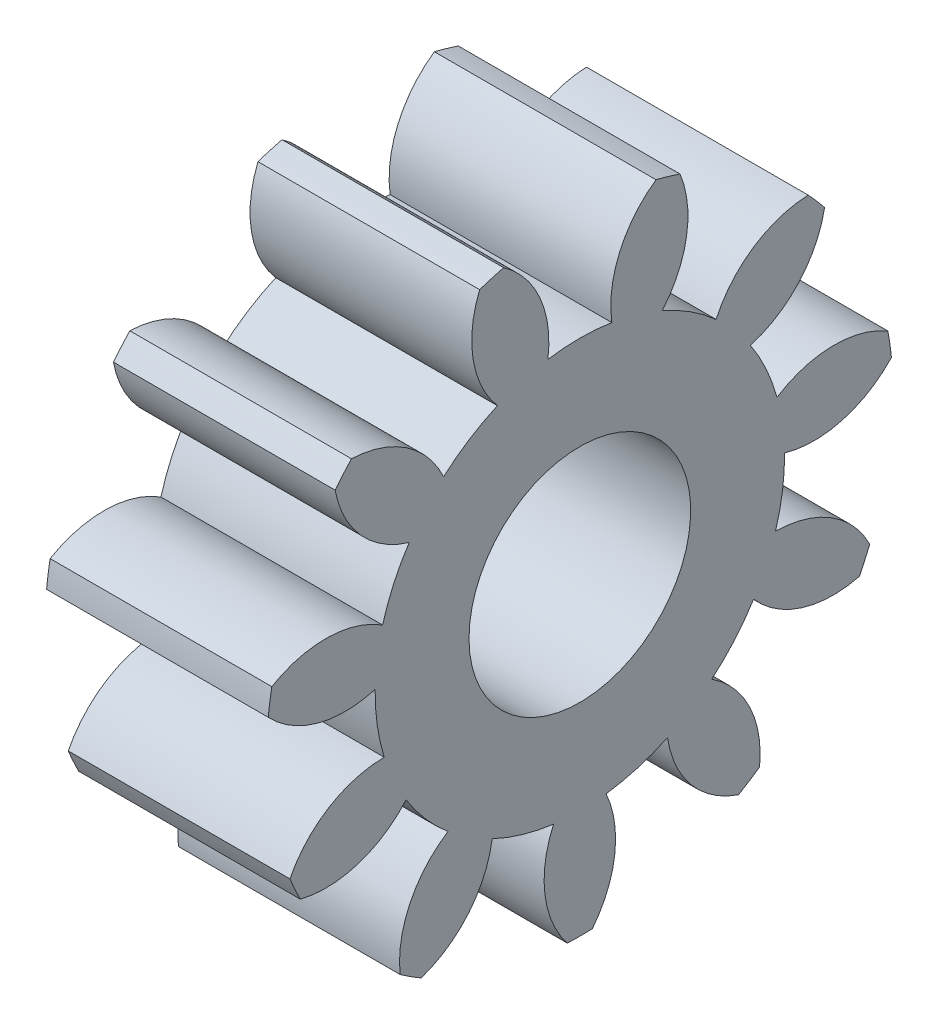
SolidWorks part; units mm, degrees
ref_plane "Plane1" through (0, 0, 0) normal (0, 0, 1) x (1, 0, 0)
ref_plane "Plane2" through (0, 0, 0) normal (0, 1, 0) x (1, 0, 0)
ref_plane "Plane3" through (0, 0, 0) normal (1, 0, 0) x (0, 0, -1)
other "Configuration Table"
sketch "HoldingSke" plane through (0, 0, 0) normal (0, 1, 0) x (1, 0, 0)
  line L0 (0, 0) -> (1.9633, -0.3816)
  line L1 (-15, 0) -> (100, 0) construction
  line L2 (0, 0) -> (-2.1039, 2.3779)
  line L3 (0, 0) -> (-11.863, 4.5341)
  line L4 (0, 0) -> (8.4773, 1.6478)
  line L5 (0, 0) -> (-46.8476, -17.4728)
  line L6 (0, 0) -> (-1.9066, -1.2864)
  line L7 (-2.1039, 2.3779) -> (8.6587, 51.2063)
  line L8 (-76.2, 54.61) -> (-75.9, 54.61)
  line L9 (-67.7845, 28.3722) -> (-49.3413, 33.142)
  line L10 (-76.2, 71.12) -> (104.1128, 71.12)
  line L11 (0, 0) -> (-2.3, 0)
  line L12 (-76.2, 101.6) -> (-76.181, 101.6)
  line L13 (24.9733, 27.94) -> (52.9518, 28.4284)
  line L14 (24.9733, 27.94) -> (24.9743, 27.94)
  line L15 (24.9733, 27.94) -> (100.4006, 29.5858)
  line L16 (-63.627, -0.5) -> (-12.827, -0.5)
  circle A0 centre (0, 0) radius 1
  circle A1 centre (0, 0) radius 2.124
  circle A2 centre (0, 0) radius 37.5
  circle A3 centre (0, 0) radius 1.15
  dimension "MHD" = 4.248
  dimension "Hub_dia" = 75
  dimension "Bore" = 2
  dimension "MBD" = 2.3
  dimension "Num_teeth" = 11
  dimension "Pitch" = 2
  dimension "Overall_len" = 50
  dimension "Show_teeth" = 11
  dimension "Thickness" = 2.3
  dimension "OAL" = 50.0005
  dimension "T_dim" = 0.3
  dimension "Ap" = 14.5
  dimension "H" = 19.05
  dimension "Pitch_radius" = 180.3128
  dimension "Width" = 2.3
  dimension "Backlash" = 0.019
  dimension "Addendum_fac" = 1
  dimension "Dedendum_fac" = 1.25
  dimension "Clearance_fac" = 0.25
  dimension "Dedendum_add" = 0.001
  dimension "Module" = 0.5
sketch "BasProSke" plane through (0, 0, 0) normal (0, 1, 0) x (1, 0, 0)
  line L0 (-10, 0) -> (60, 0) construction
  line L1 (0, 0) -> (0, 3.25)
  line L2 (0, 0) -> (2.3, 0)
  line L3 (2.3, 0) -> (2.3, 3.25)
  line L4 (2.3, 3.25) -> (0, 3.25)
  dimension "Thickness" = 2.3
  dimension "Diameter" = 6.5
revolve "Base-Revolve" add sketch "BasProSke" angle 360 about L0
sketch "TooCutSke" plane through (0, 0, 0) normal (1, 0, 0) x (0, 0, -1)
  line L1 (0, 0) -> (0, 107) construction
  line L2 (0, 0) -> (-0.4246, 2.717) construction
  line L3 (0, 0) -> (-1.5363, 5.2323) construction
  line L4 (-0.4246, 2.717) -> (-0.7682, 2.6161) construction
  arc A0 (0.3319, 2.0979) -> (-0.3319, 2.0979) centre (0, 0) ccw
  arc A1 (0.8183, 3.1715) -> (-0.8183, 3.1715) centre (0, 0) ccw
  circle A2 centre (0, 0) radius 2.75 construction
  circle A3 centre (0, 0) radius 2.6624 construction
  arc A4 (-0.3319, 2.0979) -> (-0.8183, 3.1715) centre (-1.4211, 2.2514) ccw
  arc A5 (0.8183, 3.1715) -> (0.3319, 2.0979) centre (1.4211, 2.2514) ccw
  dimension "Root_dia" = 4.248
  dimension "Overcut_dia" = 6.5508
  dimension "Pitch_dia" = 5.5
  dimension "Base_dia" = 5.3248
  dimension "Flank_rad" = 1.1
  dimension "Half_ang" = 16.364
  dimension "Half_CT" = 0.3581
extrude "ToothCut" cut sketch "TooCutSke" along normal through all
fillet "Breaks" [suppressed] radius 0.01
fillet "RootFillets" [suppressed] radius 0.126
pattern_circular "TeethCuts" count 11 over 360 about axis through (0, 0, 0) along (1, 0, 0) of "ToothCut", "RootFillets", "Breaks"
sketch "HubNeaOneSke" plane through (0, 0, 0) normal (-1, 0, 0) x (0, 0, 1)
  circle A0 centre (0, 0) radius 2.124
  dimension "Diameter" = 4.248
extrude "HubNearOne" [suppressed] add sketch "HubNeaOneSke" along normal blind 47.7005
sketch "HubNeaBotSke" plane through (0, 0, 0) normal (-1, 0, 0) x (0, 0, 1)
  circle A0 centre (0, 0) radius 2.124
  dimension "Diameter" = 4.248
extrude "HubNearBoth" [suppressed] add sketch "HubNeaBotSke" along normal blind 23.8503
ref_plane "FarPln" through (2.3, 0, 0) normal (1, 0, 0) x (0, 0, -1)
sketch "HubFarSke" plane through (2.3, 0, 0) normal (1, 0, 0) x (0, 0, -1)
  circle A0 centre (0, 0) radius 2.124
  dimension "Diameter" = 4.248
extrude "HubFar" [suppressed] add sketch "HubFarSke" along normal blind 23.8503
sketch "BorSke" plane through (0, 0, 0) normal (1, 0, 0) x (0, 0, -1)
  circle A0 centre (0, 0) radius 1.15
  dimension "Diameter" = 2.3
extrude "Bore" cut sketch "BorSke" along normal mid plane 100.001
sketch "KeySke" plane through (0, 0, 0) normal (1, 0, 0) x (0, 0, -1)
  line L0 (-0.4, 0) -> (-0.4, 1.45)
  line L1 (-0.4, 1.45) -> (0.4, 1.45)
  line L2 (0.4, 1.45) -> (0.4, 0)
  line L3 (0, 0) -> (0, 34) construction
  line L4 (-0.4, 0) -> (0.4, 0)
  dimension "Offset" = 1.45
  dimension "Width" = 0.8
extrude "Keyway" [suppressed] cut sketch "KeySke" along normal mid plane 100.001
pattern_circular "Keyway2" [suppressed] count 2 every 90 about axis through (-10, 0, 0) along (1, 0, 0)
equation "' \"Module@HoldingSke\" = 6.35"
equation "' \"Num_teeth@HoldingSke\" = 12"
equation "' \"Ap@HoldingSke\" =  20"
equation "' \"Ap@HoldingSke\" = 20"
equation "' \"Width@HoldingSke\" = 0.5 * 25.4"
equation "' \"Hub_dia@HoldingSke\"= 1 * 25.4"
equation "' \"Hub_dia@HoldingSke\" = 1 * 25.4"
equation "' \"Overall_len@HoldingSke\" = 1.0 * 25.4"
equation "' \"Bore@HoldingSke\" = 0.75 * 25.4"
equation "' \"T_dim@HoldingSke\" = 0.1 * 25.4"
equation "' \"Width@KeySke\" = 0.25 * 25.4"
equation "' \"Show_teeth@HoldingSke\" = 13"
equation "' \"Backlash@HoldingSke\" = 0.009 * 25.4"
equation "' \"Addendum_fac@HoldingSke\" = 1.0"
equation "' \"Dedendum_fac@HoldingSke\" = 1.25"
equation "' \"Dedendum_add@HoldingSke\" = 0.00005 * 25.4"
equation "' \"Clearance_fac@HoldingSke\" = 0.25"
equation "\"Pitch@HoldingSke\" = 1 / \"Module@HoldingSke\""
equation "\"Overcut_dia@TooCutSke\" = (\"Num_teeth@HoldingSke\" + 2 * \"Addendum_fac@HoldingSke\") / \"Pitch@HoldingSke\" + 0.002 * 25.4"
equation "\"Pitch_dia@TooCutSke\" = \"Num_teeth@HoldingSke\" / \"Pitch@HoldingSke\""
equation "\"Base_dia@TooCutSke\" = \"Num_teeth@HoldingSke\" / \"Pitch@HoldingSke\" * cos((\"Ap@HoldingSke\"  * 3.14159265 / 180))"
equation "\"Root_dia@TooCutSke\" = (\"Num_teeth@HoldingSke\" + 2) / \"Pitch@HoldingSke\" - 2 * (\"Addendum_fac@HoldingSke\" + \"Dedendum_fac@HoldingSke\") / \"Pitch@HoldingSke\" - \"Dedendum_add@HoldingSke\" * 2"
equation "\"Half_ang@TooCutSke\" = 180 / \"Num_teeth@HoldingSke\""
equation "\"Half_CT@TooCutSke\" = \"Num_teeth@HoldingSke\" / \"Pitch@HoldingSke\" * sin((3.14159265 / 2 / \"Num_teeth@HoldingSke\")) / 2 - 7 * \"Backlash@HoldingSke\" / 4"
equation "\"Flank_rad@TooCutSke\" = \"Num_teeth@HoldingSke\" / \"Pitch@HoldingSke\" / 5"
equation "\"Radius@RootFillets\" = \"Clearance_fac@HoldingSke\" / \"Pitch@HoldingSke\" + \"Dedendum_add@HoldingSke\""
equation "\"Break_rad@Breaks\" = 0.02 / \"Pitch@HoldingSke\""
equation "\"Thickness@HoldingSke\" = \"Width@HoldingSke\""
equation "\"OAL@HoldingSke\" = \"Thickness@HoldingSke\""
equation "\"MHD@HoldingSke\" = (\"Num_teeth@HoldingSke\" + 2) / \"Pitch@HoldingSke\" - 2 * (\"Addendum_fac@HoldingSke\" + \"Dedendum_fac@HoldingSke\")  / \"Pitch@HoldingSke\" - \"Dedendum_add@HoldingSke\" * 2"
equation "\"MHD@HoldingSke\" = ((sgn( \"MHD@HoldingSke\" - \"Hub_dia@HoldingSke\" )-1)*( \"MHD@HoldingSke\" - \"Hub_dia@HoldingSke\" ))/-2+ \"Hub_dia@HoldingSke\""
equation "\"OAL@HoldingSke\" = ((sgn( \"OAL@HoldingSke\" - \"Overall_len@HoldingSke\" )+1)*( \"OAL@HoldingSke\" - \"Overall_len@HoldingSke\" ))/2 + \"Overall_len@HoldingSke\" + 0.000002 * 25.4"
equation "\"Num_teeth@TeethCuts\" = int( \"Show_teeth@HoldingSke\" ) + 1"
equation "\"Num_teeth@TeethCuts\" = ((sgn( \"Num_teeth@TeethCuts\" - \"Num_teeth@HoldingSke\" )-1)*( \"Num_teeth@TeethCuts\" - \"Num_teeth@HoldingSke\" ))/-2+ \"Num_teeth@HoldingSke\""
equation "\"Num_teeth@TeethCuts\" = ((sgn( \"Num_teeth@TeethCuts\" - 2.0)+1)*( \"Num_teeth@TeethCuts\" - 2.0))/2 +2.0"
equation "\"Angle@TeethCuts\" = 360.0 / \"Num_teeth@HoldingSke\""
equation "\"Diameter@BasProSke\" = (\"Num_teeth@HoldingSke\" + 2 * \"Addendum_fac@HoldingSke\") / \"Pitch@HoldingSke\""
equation "\"Thickness@BasProSke\"  = \"Thickness@HoldingSke\""
equation "' \"Fillet_rad@BasProSke\" =  \"Thickness@HoldingSke\" * 0.05"
equation "' \"Fillet_rad@BasProSke\" = \"Thickness@HoldingSke\" * 0.05"
equation "\"MHD@HoldingSke\" = ((sgn( \"MHD@HoldingSke\" - \"Root_dia@TooCutSke\" )-1)*( \"MHD@HoldingSke\" - \"Root_dia@TooCutSke\" ))/-2+ \"Root_dia@TooCutSke\""
equation "\"Diameter@HubNeaOneSke\" = \"MHD@HoldingSke\""
equation "\"Length@HubNearOne\" = \"OAL@HoldingSke\" - \"Thickness@BasProSke\""
equation "\"Diameter@HubNeaBotSke\" = \"MHD@HoldingSke\""
equation "\"Length@HubNearBoth\" = ( \"OAL@HoldingSke\" - \"Thickness@BasProSke\" ) / 2.0"
equation "\"Thickness@FarPln\" = \"Thickness@BasProSke\""
equation "\"Diameter@HubFarSke\" = \"MHD@HoldingSke\""
equation "\"Length@HubFar\" = ( \"OAL@HoldingSke\" - \"Thickness@BasProSke\" ) / 2.0"
equation "\"Diameter@BorSke\" = \"MBD@HoldingSke\""
equation "\"D1@Bore\" = \"OAL@HoldingSke\" * 2.0"
equation "\"D1@Keyway\" = \"OAL@HoldingSke\" * 2.0"
equation "\"Offset@KeySke\" = \"T_dim@HoldingSke\" + \"MBD@HoldingSke\" / 2.0"
